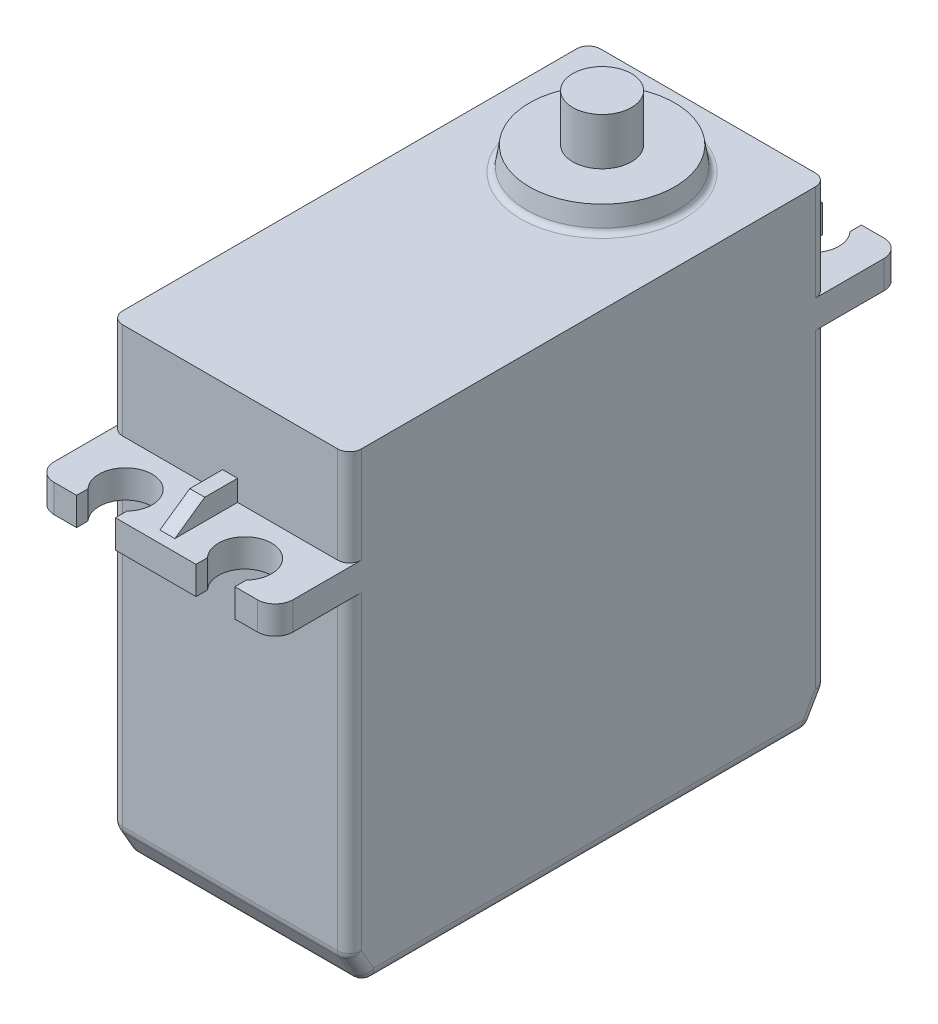
SolidWorks part; units mm, degrees
ref_plane "Front Plane" through (0, 0, 0) normal (0, 0, 1) x (1, 0, 0)
ref_plane "Top Plane" through (0, 0, 0) normal (0, 1, 0) x (1, 0, 0)
ref_plane "Right Plane" through (0, 0, 0) normal (1, 0, 0) x (0, 0, -1)
sketch "Sketch1" plane through (0, 0, 0) normal (0, 1, 0) x (1, 0, 0)
  line L1 (-10.16, 10.16) -> (10.16, 10.16)
  line L2 (-10.16, 10.16) -> (-10.16, -30.48)
  line L3 (-10.16, -30.48) -> (10.16, -30.48)
  line L4 (10.16, 10.16) -> (10.16, -30.48)
  dimension "D1" = 20.32
  dimension "D2" = 40.64
  dimension "D3" = 10.16
  dimension "D4" = 10.16
extrude "Extrude1" add sketch "Sketch1" along normal blind 29.2
sketch "Sketch2" plane through (0, 29.2, 0) normal (0, 1, 0) x (-1, 0, 0)
  line L0 (10.16, 30.48) -> (10.16, 36.8046)
  line L1 (10.16, 36.8046) -> (6.731, 36.8046)
  line L2 (-10.16, 36.8046) -> (-10.16, 30.48)
  line L3 (10.16, -10.16) -> (10.16, -16.4846)
  line L4 (10.16, -10.16) -> (10.16, 30.48)
  line L5 (10.16, 30.48) -> (-10.16, 30.48)
  line L6 (-10.16, 30.48) -> (-10.16, -10.16)
  line L7 (-10.16, -10.16) -> (10.16, -10.16)
  line L8 (10.16, -10.16) -> (10.16, 30.48)
  line L9 (10.16, 30.48) -> (-10.16, 30.48)
  line L10 (-10.16, 30.48) -> (-10.16, -10.16)
  line L11 (-10.16, -10.16) -> (10.16, -10.16)
  line L12 (10.16, -16.4846) -> (6.731, -16.4846)
  line L13 (-10.16, -16.4846) -> (-10.16, -10.16)
  line L14 (-6.731, 35.8342) -> (-6.731, 36.8046)
  line L15 (-3.429, 35.8342) -> (-3.429, 36.8046)
  line L16 (3.429, 35.8342) -> (3.429, 36.8046)
  line L17 (6.731, 35.8342) -> (6.731, 36.8046)
  line L18 (6.731, -15.5142) -> (6.731, -16.4846)
  line L19 (3.429, -15.5142) -> (3.429, -16.4846)
  line L20 (-3.429, -15.5142) -> (-3.429, -16.4846)
  line L21 (-6.731, -15.5142) -> (-6.731, -16.4846)
  line L22 (-6.731, -16.4846) -> (-10.16, -16.4846)
  line L23 (3.429, -16.4846) -> (-3.429, -16.4846)
  line L24 (-6.731, 36.8046) -> (-10.16, 36.8046)
  line L25 (3.429, 36.8046) -> (-3.429, 36.8046)
  arc A0 (3.429, 35.8342) -> (6.731, 35.8342) centre (5.08, 34.29) ccw
  arc A1 (-6.731, 35.8342) -> (-3.429, 35.8342) centre (-5.08, 34.29) ccw
  arc A2 (-3.429, -15.5142) -> (-6.731, -15.5142) centre (-5.08, -13.97) ccw
  arc A3 (6.731, -15.5142) -> (3.429, -15.5142) centre (5.08, -13.97) ccw
  line M5 (10.16, -10.16) -> (10.16, 30.48)
  line M6 (10.16, 30.48) -> (-10.16, 30.48)
  line M7 (-10.16, 30.48) -> (-10.16, -10.16)
  line M8 (-10.16, -10.16) -> (10.16, -10.16)
  dimension "D2" = 4.5212
  dimension "D9" = 3.302
  dimension "D3" = 5.08
  dimension "D4" = 10.16
  dimension "D5" = 48.26
  dimension "D6" = 3.81
  dimension "D7" = 6.3246
  dimension "D8" = 6.3246
  dimension "D10" = 3.302
  dimension "D11" = 1.651
  dimension "D12" = 1.651
  dimension "D1" = 0
extrude "Extrude2" add sketch "Sketch2" along normal blind 2.3813 contours M8 M5 M6 M7 | A3 L18 L12 L3 L13 L22 L21 A2 L20 L23 L19 M8 | A1 L14 L24 L2 L0 L1 L17 A0 L16 L25 L15 M6
sketch "Sketch3" plane through (0, 31.5812, 0) normal (0, 1, 0) x (-1, 0, 0)
  line L4 (10.16, -10.16) -> (10.16, 30.48)
  line L5 (-10.16, -10.16) -> (10.16, -10.16)
  line L6 (-10.16, 30.48) -> (-10.16, -10.16)
  line L7 (10.16, 30.48) -> (-10.16, 30.48)
  line L8 (10.16, -10.16) -> (10.16, 30.48)
  line L9 (-10.16, -10.16) -> (10.16, -10.16)
  line L10 (-10.16, 30.48) -> (-10.16, -10.16)
  line L11 (10.16, 30.48) -> (-10.16, 30.48)
  dimension "D1" = 0
extrude "Extrude3" add sketch "Sketch3" along normal blind 8.2
ref_plane "Plane1" through (0, 38.1, 0) normal (0, -1, 0) x (1, 0, 0)
sketch "Sketch7" plane through (0, 0, 0) normal (1, 0, 0) x (0, 0, -1)
  line L0 (15.494, 31.5812) -> (12.954, 33.3592)
  line L4 (12.954, 33.3592) -> (10.16, 33.3592)
  line L5 (10.16, 39.7812) -> (10.16, 31.5812) construction
  line L6 (16.4846, 31.5812) -> (10.16, 31.5812) construction
  line L7 (10.16, 33.3592) -> (10.16, 31.5812)
  line L8 (10.16, 31.5812) -> (15.494, 31.5812)
  dimension "D1" = 1.778
  dimension "D2" = 2.794
  dimension "D3" = 5.334
extrude "Extrude6" add sketch "Sketch7" along normal mid plane 1.27
ref_plane "Plane2" through (0, 0, 10.16) normal (0, 0, -1) x (-1, 0, 0)
mirror "Mirror1" about plane through (0, 0, 10.16) normal (0, 0, -1) of "Extrude6"
chamfer "Chamfer2" distance 2.54 angle 30 2 edges at (0, 0, 30.48) (0, 0, -10.16)
fillet "Fillet1" radius 1.016 18 edges at (10.16, 0, 10.16) (10.16, 1.27, -9.4268) (0, 0, -8.6935) (0, 2.54, -10.16) (-10.16, 1.27, -9.4268) (10.16, 1.27, 29.7468) (0, 2.54, 30.48) (-10.16, 0, 10.16) (0, 0, 29.0135) (-10.16, 1.27, 29.7468)
fillet "Fillet2" radius 1.524 4 edges at (-10.16, 30.3906, 36.8046) (10.16, 30.3906, 36.8046) (-10.16, 30.3906, -16.4846) (10.16, 30.3906, -16.4846)
sketch "Sketch9" plane through (0, 0, -10.16) normal (0, 0, -1) x (-1, 0, 0)
  line L1 (-3.175, 12.54) -> (3.175, 12.54)
  line L2 (-3.175, 12.54) -> (-3.175, 10)
  line L3 (-3.175, 10) -> (3.175, 10)
  line L4 (3.175, 12.54) -> (3.175, 10)
  dimension "D1" = 6.35
  dimension "D2" = 2.54
  dimension "D3" = 10
  dimension "D4" = 3.175
extrude "Extrude8" add sketch "Sketch9" along normal blind 2.3813
sketch "Sketch10" plane through (0, 0, -12.5412) normal (0, 0, -1) x (-1, 0, 0)
  line L8 (-2.54, 11.905) -> (-2.54, 10.635)
  line L9 (-2.54, 10.635) -> (2.54, 10.635)
  line L10 (2.54, 10.635) -> (2.54, 11.905)
  line L11 (2.54, 11.905) -> (-2.54, 11.905)
  line L12 (-2.54, 11.905) -> (-2.54, 10.635)
  line L13 (-2.54, 10.635) -> (2.54, 10.635)
  line L14 (2.54, 10.635) -> (2.54, 11.905)
  line L15 (2.54, 11.905) -> (-2.54, 11.905)
  dimension "D1" = 0.635
extrude "Cut-Extrude1" cut sketch "Sketch10" against normal up to surface (2.3813 mm away) up to face at (2.286, 16.0061, -10.16)
sketch "Эскиз1" plane through (0, 39.7812, 0) normal (0, 1, 0) x (1, 0, 0)
  line L0 (9.144, 10.16) -> (0.635, 10.16) construction
  circle A0 centre (0, 1.16) radius 6.5
  dimension "D1" = 9
extrude "Вытянуть1" add sketch "Эскиз1" along normal blind 2 draft 9
fillet "Скругление1" radius 0.5 1 edges at (0, 39.7812, 5.34)
sketch "Эскиз2" plane through (0, 41.7812, 0) normal (0, 1, 0) x (1, 0, 0)
  circle A0 centre (0, 1.16) radius 2.5
extrude "Вытянуть2" add sketch "Эскиз2" along normal blind 4
